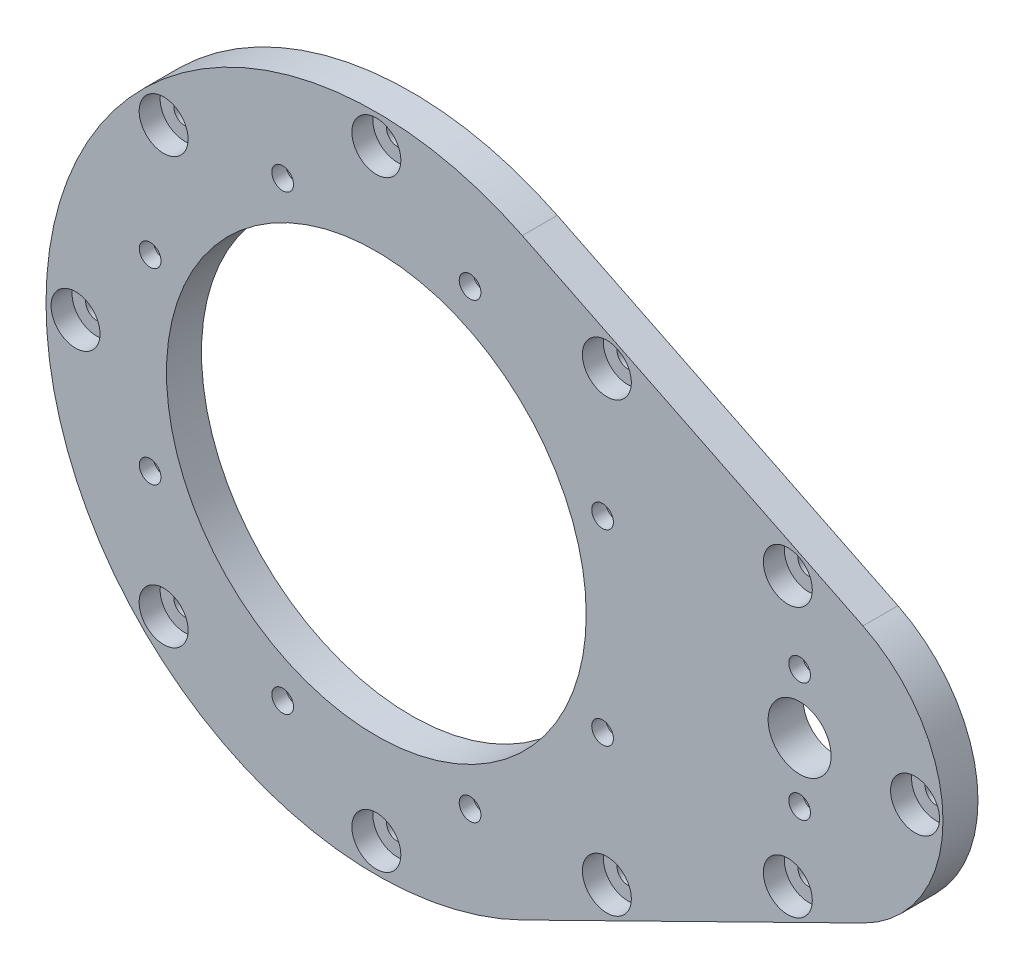
SolidWorks part; units mm, degrees
ref_plane "Front Plane" through (0, 0, 0) normal (0, 0, 1) x (1, 0, 0)
ref_plane "Top Plane" through (0, 0, 0) normal (0, 1, 0) x (1, 0, 0)
ref_plane "Right Plane" through (0, 0, 0) normal (1, 0, 0) x (0, 0, -1)
sketch "Sketch1" plane through (0, 0, 0) normal (0, 0, 1) x (1, 0, 0)
  line L0 (60.5, -8.5) -> (60.5, 8.5) construction
  line L1 (0, 0) -> (60.5, 0) construction
  line L6 (69.5542, 18.3922) -> (20.8559, 42.3656)
  line L7 (69.5542, -18.3922) -> (20.8559, -42.3656)
  line L8 (0, 0) -> (0, 43) construction
  line L9 (0, 0) -> (32.3358, 13.3939) construction
  line L10 (20.8559, 42.3656) -> (34.716, 35.5424) construction
  line L11 (34.716, 35.5424) -> (32.9494, 31.9537) construction
  line L12 (69.5542, 18.3922) -> (60.5824, 22.8088) construction
  line L13 (60.5824, 22.8088) -> (58.8157, 19.2201) construction
  line L14 (20.8559, -42.3656) -> (34.716, -35.5424) construction
  line L15 (34.716, -35.5424) -> (32.9494, -31.9537) construction
  line L16 (69.5542, -18.3922) -> (60.5824, -22.8088) construction
  line L17 (60.5824, -22.8088) -> (58.8157, -19.2201) construction
  line L18 (60.5, 0) -> (77, 0) construction
  circle A1 centre (0, 0) radius 47.2208 construction
  circle A11 centre (60.5, 0) radius 20.5 construction
  circle A14 centre (60.5, 8.5) radius 1.55
  circle A15 centre (60.5, -8.5) radius 1.55
  circle A16 centre (60.5, 0) radius 4.5
  circle A17 centre (0, 0) radius 30
  circle A18 centre (0, 0) radius 35 construction
  arc A27 (69.5542, 18.3922) -> (69.5542, -18.3922) centre (60.5, 0) cw
  arc A28 (20.8559, 42.3656) -> (20.8559, -42.3656) centre (0, 0) ccw
  circle A29 centre (0, 43) radius 1.55
  circle A30 centre (-30.4056, 30.4056) radius 1.55
  circle A31 centre (-43, 0) radius 1.55
  circle A32 centre (-30.4056, -30.4056) radius 1.55
  circle A33 centre (0, -43) radius 1.55
  circle A34 centre (32.3358, 13.3939) radius 1.55
  circle A35 centre (32.3358, -13.3939) radius 1.55
  circle A36 centre (13.3939, -32.3358) radius 1.55
  circle A37 centre (-13.3939, -32.3358) radius 1.55
  circle A38 centre (-32.3358, -13.3939) radius 1.55
  circle A39 centre (-32.3358, 13.3939) radius 1.55
  circle A40 centre (-13.3939, 32.3358) radius 1.55
  circle A41 centre (13.3939, 32.3358) radius 1.55
  circle A42 centre (32.9494, 31.9537) radius 1.55
  circle A43 centre (58.8157, 19.2201) radius 1.55
  circle A44 centre (32.9494, -31.9537) radius 1.55
  circle A45 centre (58.8157, -19.2201) radius 1.55
  circle A46 centre (77, 0) radius 1.55
  point P7 (60.5, 0)
  point P22 (0, 0)
  point P30 (0, 0)
  point P36 (0, 0)
  point P48 (0, 0)
extrude "Boss-Extrude2" add sketch "Sketch1" along normal blind 5
sketch "Sketch2" plane through (0, 0, 0) normal (0, 0, -1) x (-1, 0, 0)
  circle A0 centre (-60.5, 8.5) radius 3.5
  circle A1 centre (-60.5, -8.5) radius 3.5
  circle A10 centre (-13.3939, 32.3358) radius 3.5
  circle A11 centre (13.3939, 32.3358) radius 3.5
  circle A12 centre (32.3358, 13.3939) radius 3.5
  circle A13 centre (32.3358, -13.3939) radius 3.5
  circle A14 centre (13.3939, -32.3358) radius 3.5
  circle A15 centre (-13.3939, -32.3358) radius 3.5
  circle A16 centre (-32.3358, -13.3939) radius 3.5
  circle A17 centre (-32.3358, 13.3939) radius 3.5
  point P25 (0, 0)
extrude "Cut-Extrude1" cut sketch "Sketch2" against normal blind 3
sketch "Sketch3" plane through (0, 0, 5) normal (0, 0, 1) x (1, 0, 0)
  circle A0 centre (0, 43) radius 3.5
  circle A1 centre (-30.4056, 30.4056) radius 3.5
  circle A2 centre (-43, 0) radius 3.5
  circle A3 centre (-30.4056, -30.4056) radius 3.5
  circle A4 centre (0, -43) radius 3.5
  circle A5 centre (32.9494, 31.9537) radius 3.5
  circle A6 centre (58.8157, 19.2201) radius 3.5
  circle A7 centre (32.9494, -31.9537) radius 3.5
  circle A8 centre (58.8157, -19.2201) radius 3.5
  circle A9 centre (77, 0) radius 3.5
  point P13 (0, 0)
extrude "Cut-Extrude2" cut sketch "Sketch3" against normal blind 3
